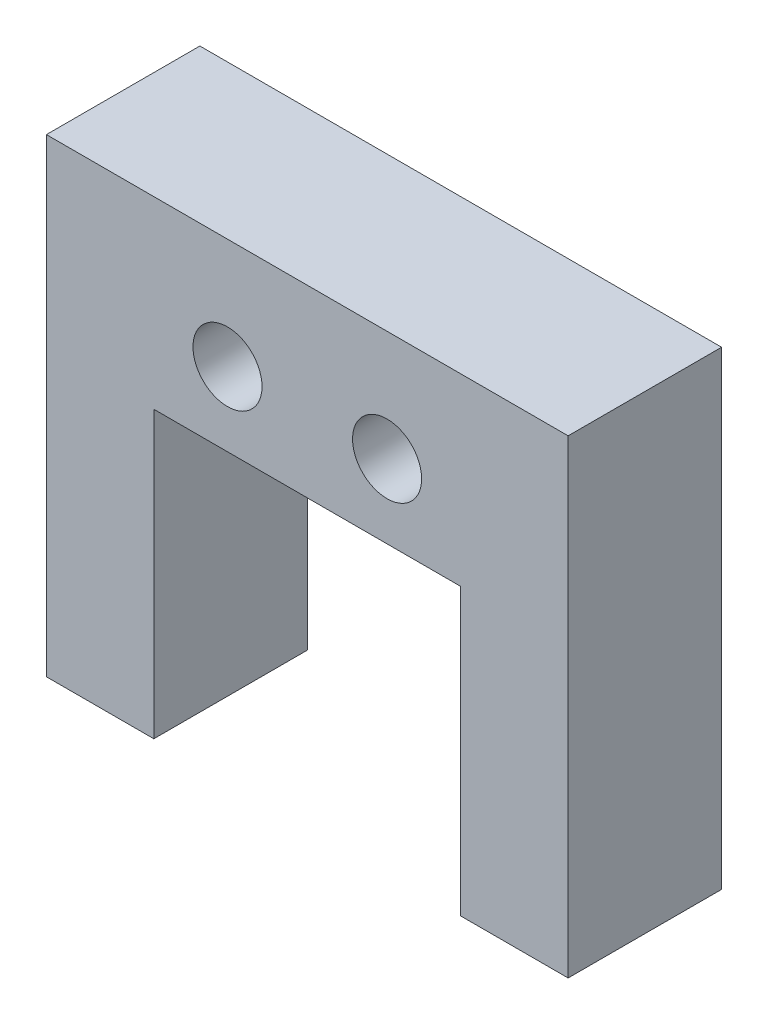
SolidWorks part; units mm, degrees
ref_plane "Front Plane" through (0, 0, 0) normal (0, 0, 1) x (1, 0, 0)
ref_plane "Top Plane" through (0, 0, 0) normal (0, 1, 0) x (1, 0, 0)
ref_plane "Right Plane" through (0, 0, 0) normal (1, 0, 0) x (0, 0, -1)
sketch "Sketch1" plane through (0, 0, 0) normal (0, 0, 1) x (1, 0, 0)
  line L0 (27, 0) -> (34, 0)
  line L1 (0, 0) -> (7, 0)
  line L2 (0, 0) -> (0, 30.6)
  line L3 (0, 30.6) -> (34, 30.6)
  line L4 (34, 0) -> (34, 30.6)
  line L6 (7, 0) -> (7, 18.6)
  line L7 (7, 18.6) -> (27, 18.6)
  line L8 (27, 0) -> (27, 18.6)
  circle A0 centre (22.2, 23.4) radius 2.25
  circle A1 centre (11.8, 23.4) radius 2.25
  dimension "D6" = 4.5
  dimension "D1" = 30.6
  dimension "D2" = 34
  dimension "D3" = 7
  dimension "D4" = 20
  dimension "D5" = 18.6
  dimension "D7" = 4.8
  dimension "D8" = 4.8
  dimension "D9" = 10.4
extrude "Boss-Extrude1" add sketch "Sketch1" along normal blind 10
